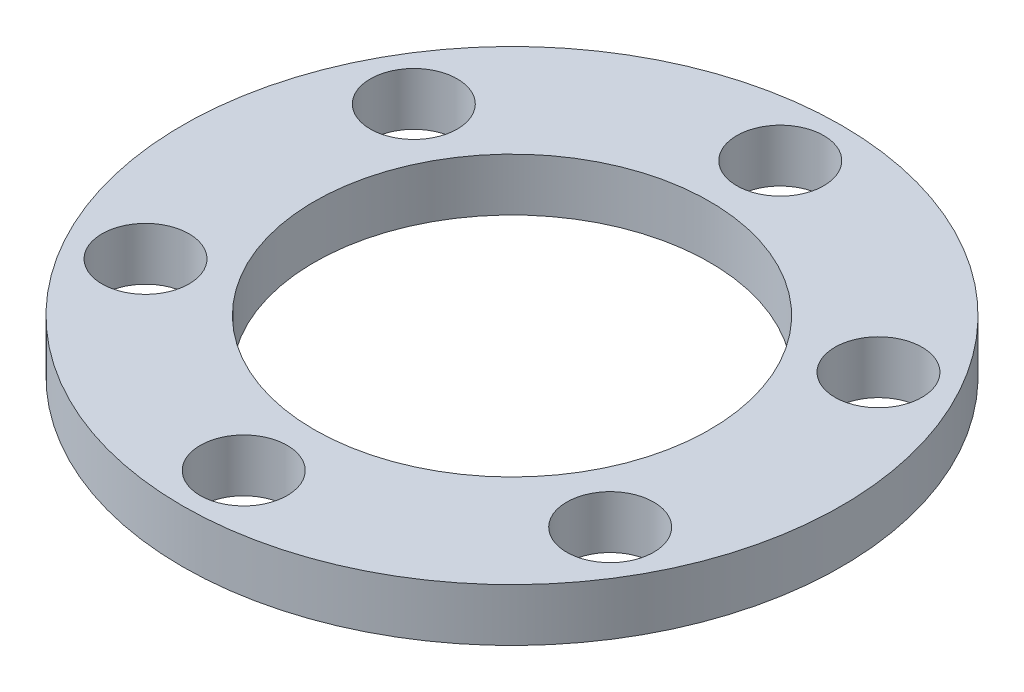
SolidWorks part; units mm, degrees
material "ABS"
ref_plane "Спереди" through (0, 0, 0) normal (0, 0, 1) x (1, 0, 0)
ref_plane "Сверху" through (0, 0, 0) normal (0, 1, 0) x (1, 0, 0)
ref_plane "Справа" through (0, 0, 0) normal (1, 0, 0) x (0, 0, -1)
sketch "Эскиз1" plane through (0, 0, 0) normal (0, 1, 0) x (1, 0, 0)
  circle A0 centre (0, 0) radius 12.5
extrude "Бобышка-Вытянуть1" add sketch "Эскиз1" along normal blind 2
sketch "Эскиз2" plane through (0, 0, 0) normal (0, -1, 0) x (1, 0, 0)
  circle A0 centre (0, -10.1761) radius 1.65
  point P2 (0, -10.1761)
extrude "Вырез-Вытянуть1" cut sketch "Эскиз2" against normal through all
pattern_circular "Круговой массив1" count 6 over 360 about axis through (0, 0, 0) along (0, 1, 0) of "Вырез-Вытянуть1"
sketch "Эскиз6" plane through (0, 2, 0) normal (0, 1, 0) x (1, 0, 0)
  circle A0 centre (0, 0) radius 7.5
extrude "Вырез-Вытянуть3" cut sketch "Эскиз6" against normal through all
